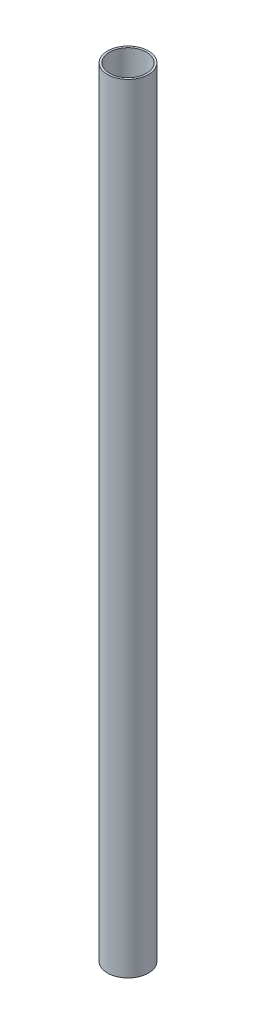
SolidWorks part; units mm, degrees
ref_plane "Front Plane" through (0, 0, 0) normal (0, 0, 1) x (1, 0, 0)
ref_plane "Top Plane" through (0, 0, 0) normal (0, 1, 0) x (1, 0, 0)
ref_plane "Right Plane" through (0, 0, 0) normal (1, 0, 0) x (0, 0, -1)
sketch "Sketch1" plane through (0, 0, 0) normal (0, 1, 0) x (1, 0, 0)
  circle A0 centre (0, 0) radius 10
  circle A1 centre (0, 0) radius 9
  dimension "D1" = 1
extrude "Boss-Extrude1" add sketch "Sketch1" along normal blind 380
